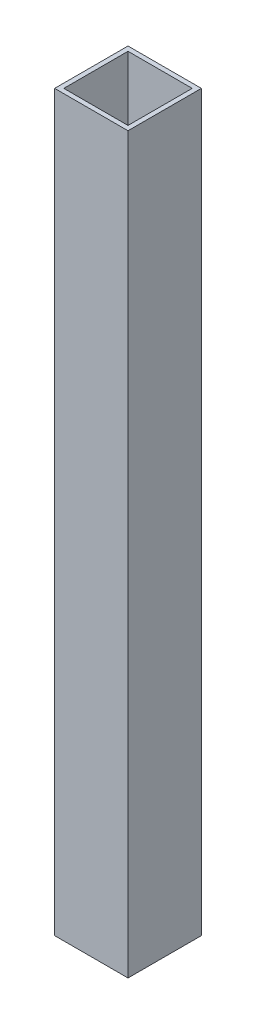
SolidWorks part; units mm, degrees
material "6061 Alloy"
ref_plane "Front Plane" through (0, 0, 0) normal (0, 0, 1) x (1, 0, 0)
ref_plane "Top Plane" through (0, 0, 0) normal (0, 1, 0) x (1, 0, 0)
ref_plane "Right Plane" through (0, 0, 0) normal (1, 0, 0) x (0, 0, -1)
sketch "Sketch1" plane through (0, 0, 0) normal (0, 1, 0) x (1, 0, 0)
  line L1 (12.7, 12.7) -> (-12.7, 12.7)
  line L2 (12.7, 12.7) -> (12.7, -12.7)
  line L3 (12.7, -12.7) -> (-12.7, -12.7)
  line L4 (-12.7, 12.7) -> (-12.7, -12.7)
  line L5 (12.7, 12.7) -> (-12.7, -12.7) construction
  line L6 (12.7, -12.7) -> (-12.7, 12.7) construction
  line L7 (11.1125, 11.1125) -> (-11.1125, 11.1125)
  line L8 (11.1125, 11.1125) -> (11.1125, -11.1125)
  line L9 (11.1125, -11.1125) -> (-11.1125, -11.1125)
  line L10 (-11.1125, 11.1125) -> (-11.1125, -11.1125)
  line L11 (11.1125, 11.1125) -> (-11.1125, -11.1125) construction
  line L12 (11.1125, -11.1125) -> (-11.1125, 11.1125) construction
  point P1 (0, 0)
  point P6 (0, 0)
  dimension "D1" = 25.4
  dimension "D2" = 25.4
  dimension "D3" = 1.5875
  dimension "D4" = 1.5875
extrude "Boss-Extrude1" add sketch "Sketch1" along normal blind 254
